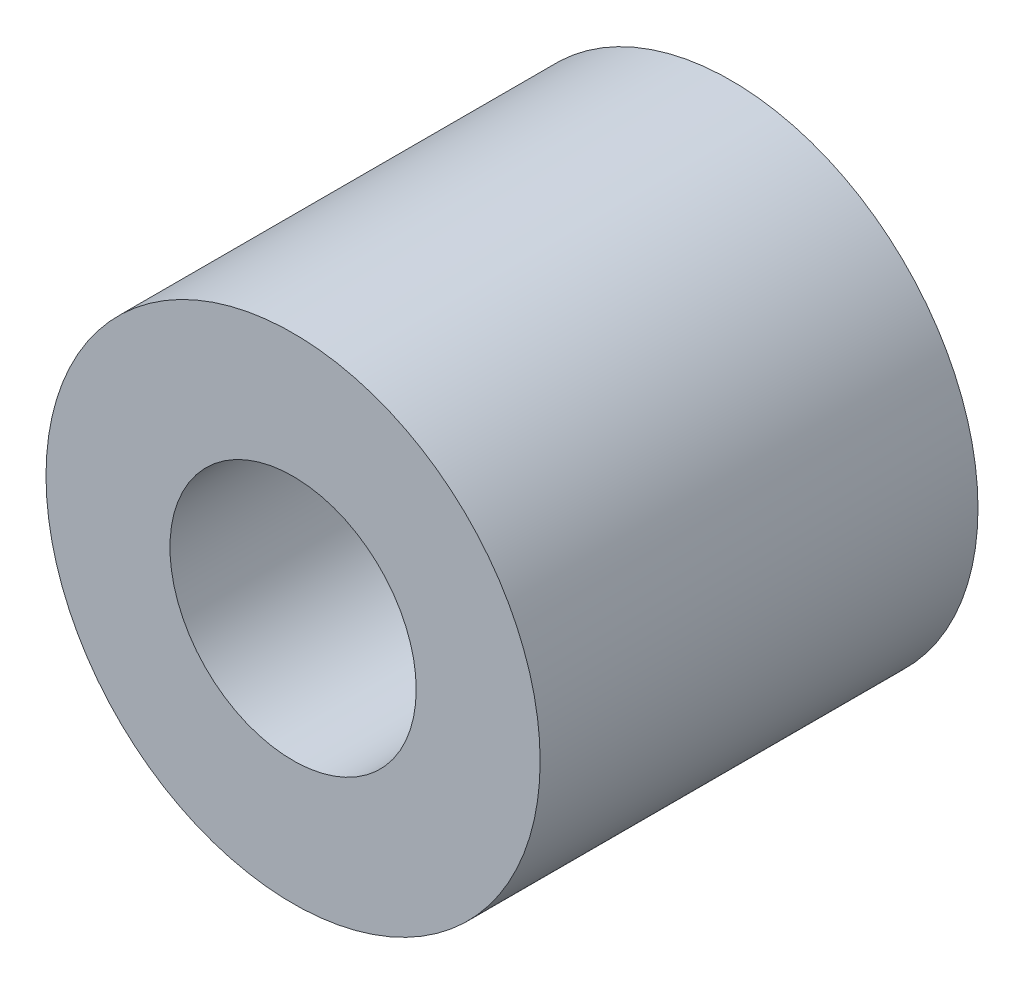
SolidWorks part; units mm, degrees
ref_plane "Front Plane" through (0, 0, 0) normal (0, 0, 1) x (1, 0, 0)
ref_plane "Top Plane" through (0, 0, 0) normal (0, 1, 0) x (1, 0, 0)
ref_plane "Right Plane" through (0, 0, 0) normal (1, 0, 0) x (0, 0, -1)
sketch "Sketch1" plane through (0, 0, 0) normal (0, 0, 1) x (1, 0, 0)
  circle A0 centre (0, 0) radius 2.5
  circle A1 centre (0, 0) radius 5.0165
  dimension "D1" = 5
  dimension "D2" = 10.033
extrude "Boss-Extrude1" add sketch "Sketch1" along normal mid plane 8.89
